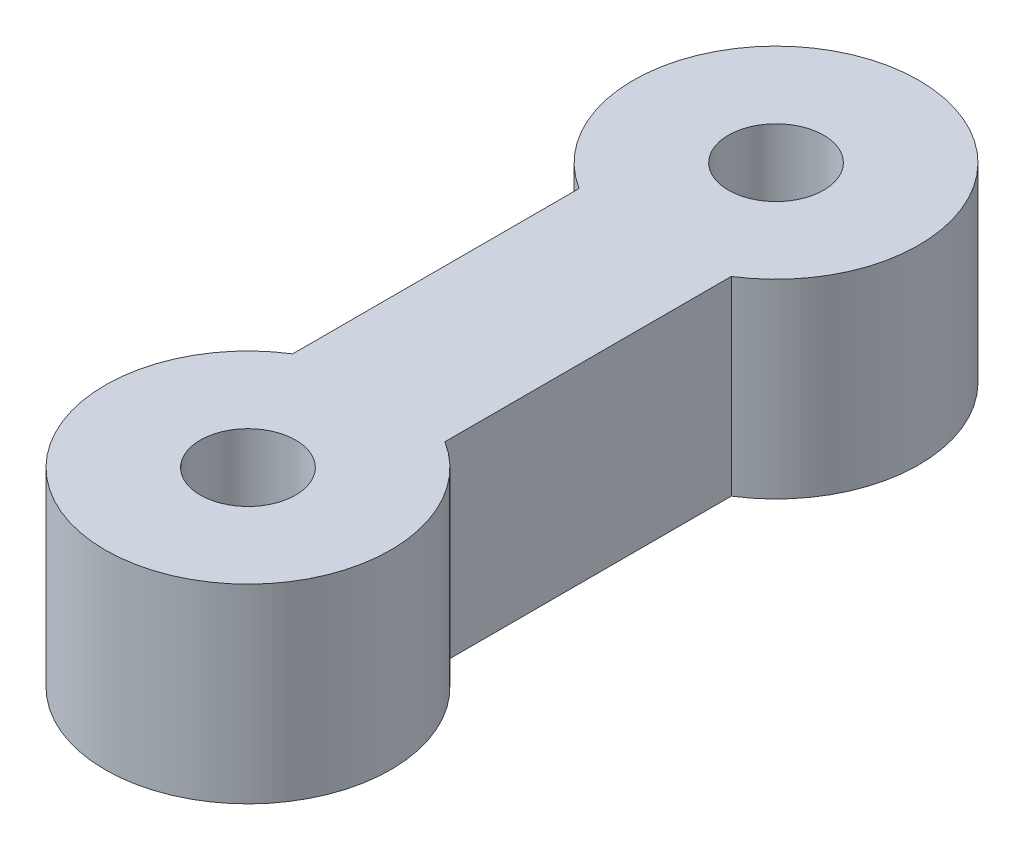
SolidWorks part; units mm, degrees
ref_plane "前基準面" through (0, 0, 0) normal (0, 0, 1) x (1, 0, 0)
ref_plane "上基準面" through (0, 0, 0) normal (0, 1, 0) x (1, 0, 0)
ref_plane "右基準面" through (0, 0, 0) normal (1, 0, 0) x (0, 0, -1)
sketch "草圖1" plane through (0, 0, 0) normal (0, 1, 0) x (1, 0, 0)
  circle A0 centre (0, 0) radius 2.505
  dimension "D1" = 5.01
extrude "伸長-薄件1" add sketch "草圖1" along normal blind 10 thin
ref_plane "平面2" through (0, 0, 13) normal (0, 0, 1) x (1, 0, 0)
sketch "草圖7" plane through (0, 0, 13) normal (0, 0, 1) x (1, 0, 0)
  line L0 (-1007.505, 5) -> (48992.495, 5) construction
  line L1 (-7.505, 10) -> (-7.505, 0) construction
  line L2 (0, -990) -> (0, 49010) construction
  line L3 (7.505, 10) -> (-7.505, 10) construction
  line L4 (-7.505, 0) -> (7.505, 0) construction
  line L5 (-4, 10) -> (4, 10)
  line L6 (-4, 10) -> (-4, 0)
  line L7 (-4, 0) -> (4, 0)
  line L8 (4, 10) -> (4, 0)
  line L9 (-4, 10) -> (4, 0) construction
  line L10 (-4, 0) -> (4, 10) construction
  point P5 (-7.505, 5)
  point P6 (0, 5)
  point P10 (0, 10)
  dimension "D1" = 8
extrude "填料-伸長3" add sketch "草圖7" along normal blind 18.25 and the other way blind 7
sketch "草圖9" plane through (0, 10, 0) normal (0, 1, 0) x (1, 0, 0)
  line L0 (4, -6.3502) -> (4, -31.25) construction
  line L1 (-4, -31.25) -> (4, -31.25)
  line L2 (-4, -31.25) -> (-4, -27.75)
  line L3 (-4, -27.75) -> (4, -27.75)
  line L4 (4, -31.25) -> (4, -27.75)
  dimension "D1" = 3.5
extrude "除料-伸長1" cut sketch "草圖9" against normal blind 18.25
sketch "草圖10" plane through (0, 10, 0) normal (0, 1, 0) x (1, 0, 0)
  line L0 (0, -2.505) -> (0, -27.75) construction
  line L1 (4, -27.75) -> (-4, -27.75) construction
  circle A0 centre (0, 0) radius 2.505 construction
  circle A1 centre (0, -27.75) radius 2.505
  dimension "D1" = 5.01
extrude "伸長-薄件4" add sketch "草圖10" against normal blind 10 thin
sketch "草圖11" plane through (0, 10, 0) normal (0, 1, 0) x (1, 0, 0)
  line L0 (2.505, -27.75) -> (-2.505, -27.75) construction
  circle A0 centre (0, -27.75) radius 2.505
extrude "除料-伸長2" cut sketch "草圖11" against normal blind 10
